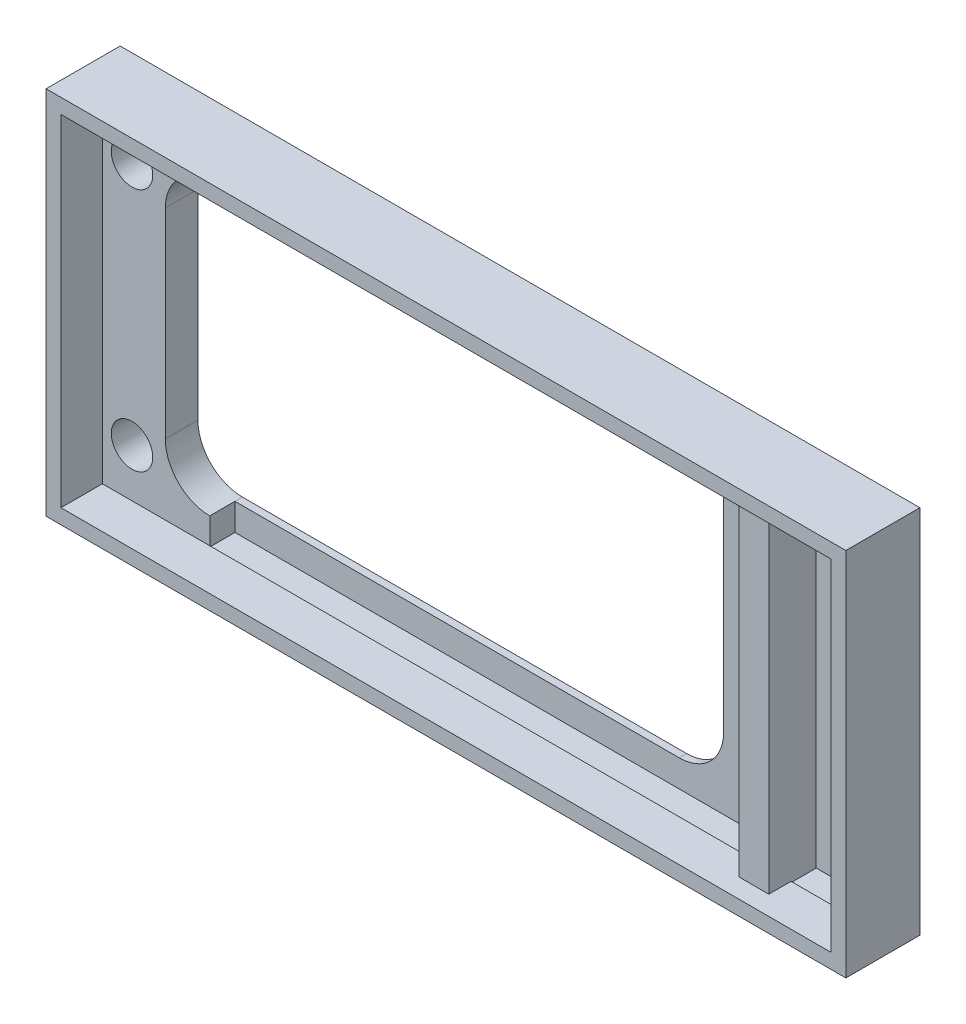
SolidWorks part; units mm, degrees
ref_plane "Front Plane" through (0, 0, 0) normal (0, 0, 1) x (1, 0, 0)
ref_plane "Top Plane" through (0, 0, 0) normal (0, 1, 0) x (1, 0, 0)
ref_plane "Right Plane" through (0, 0, 0) normal (1, 0, 0) x (0, 0, -1)
sketch "Sketch1" plane through (0, 0, 0) normal (0, 0, 1) x (1, 0, 0)
  line L1 (-26, -11.5) -> (26, -11.5)
  line L2 (-26, -11.5) -> (-26, 11.5)
  line L3 (-26, 11.5) -> (26, 11.5)
  line L4 (26, -11.5) -> (26, 11.5)
  line L5 (-26, -11.5) -> (26, 11.5) construction
  line L6 (-26, 11.5) -> (26, -11.5) construction
  line L7 (-27, -12.5) -> (27, -12.5)
  line L8 (-27, -12.5) -> (-27, 12.5)
  line L9 (-27, 12.5) -> (27, 12.5)
  line L10 (27, -12.5) -> (27, 12.5)
  line L11 (-27, -12.5) -> (27, 12.5) construction
  line L12 (-27, 12.5) -> (27, -12.5) construction
  point P0 (0, 0)
  point P6 (0, 0)
  dimension "D1" = 23
  dimension "D2" = 52
  dimension "D3" = 1
  dimension "D4" = 1
extrude "Boss-Extrude1" add sketch "Sketch1" along normal blind 5
sketch "Sketch2" plane through (0, 0, 0) normal (0, 0, -1) x (-1, 0, 0)
  line L0 (-23, 8.25) -> (-23, -8.25) construction
  line L1 (-11.25, -9.75) -> (18.75, -9.75)
  line L2 (-14.25, -6.75) -> (-14.25, 6.75)
  line L3 (-11.25, 9.75) -> (18.75, 9.75)
  line L4 (21.75, -6.75) -> (21.75, 6.75)
  line L5 (-14.25, -9.75) -> (21.75, 9.75) construction
  line L6 (-14.25, 9.75) -> (21.75, -9.75) construction
  line L7 (-27, 12.5) -> (27, 12.5) construction
  line L8 (27, -12.5) -> (-27, -12.5)
  line L9 (27, -12.5) -> (27, 12.5)
  line L10 (27, 12.5) -> (-27, 12.5)
  line L11 (-27, -12.5) -> (-27, 12.5)
  line L12 (27, -12.5) -> (-27, 12.5) construction
  line L13 (27, 12.5) -> (-27, -12.5) construction
  line L14 (-27, -12.5) -> (-27, 12.5) construction
  line L15 (26, 11.5) -> (26, -11.5) construction
  line L19 (27, 12.5) -> (27, -12.5) construction
  line L28 (27, -12.5) -> (-27, -12.5) construction
  line L29 (24, 8.25) -> (24, -8.25) construction
  arc A0 (18.75, 9.75) -> (21.75, 6.75) centre (18.75, 6.75) cw
  arc A1 (18.75, -9.75) -> (21.75, -6.75) centre (18.75, -6.75) ccw
  arc A2 (-11.25, -9.75) -> (-14.25, -6.75) centre (-11.25, -6.75) cw
  arc A3 (-14.25, 6.75) -> (-11.25, 9.75) centre (-11.25, 6.75) cw
  circle A4 centre (24, 8.25) radius 1.4
  circle A5 centre (24, -8.25) radius 1.4
  circle A6 centre (-23, 8.25) radius 1.4
  circle A7 centre (-23, -8.25) radius 1.4
  point P0 (0, 0)
  point P6 (0, 0)
  point P35 (24, 0)
  point P39 (-14.25, 0)
  point P40 (3.75, 0)
  point P44 (-23, 0)
  dimension "D3" = 3
  dimension "D4" = 2.8
  dimension "D5" = 2.8
  dimension "D6" = 2
  dimension "D7" = 2
  dimension "D8" = 36
  dimension "D9" = 16.5
  dimension "D10" = 4.25
  dimension "D11" = 4
  dimension "D12" = 16.5
  dimension "D14" = 4
  dimension "D2" = 19.5
extrude "Boss-Extrude2" add sketch "Sketch2" against normal blind 2.2
sketch "Sketch3" plane through (0, 0, 2.2) normal (0, 0, 1) x (1, 0, 0)
  line L1 (26, 11.5) -> (-18.75, 11.5)
  line L2 (26, 11.5) -> (26, -11.5719)
  line L3 (26, -11.5719) -> (-18.75, -11.5719)
  line L4 (-18.75, 11.5) -> (-18.75, -11.5719)
extrude "Cut-Extrude1" cut sketch "Sketch3" against normal blind 1.7
sketch "Sketch4" plane through (0, 0, 0.5) normal (0, 0, 1) x (1, 0, 0)
fillet "Fillet1" radius 1 1 edges at (-18.75, 10.625, 2.2)
sketch "Sketch5" plane through (0, 0, 0.5) normal (0, 0, 1) x (1, 0, 0)
  line L0 (26, 11.5) -> (-18.75, 11.5) construction
  line L1 (18.5, 11.5) -> (20.5, 11.5)
  line L2 (18.5, 11.5) -> (18.5, -11.5719)
  line L3 (18.5, -11.5719) -> (20.5, -11.5719)
  line L4 (20.5, 11.5) -> (20.5, -11.5719)
  line L5 (-18.75, -11.5719) -> (26, -11.5719) construction
  line L6 (-26, 11.5) -> (-26, -11.5) construction
  dimension "D1" = 44.5
  dimension "D2" = 2
extrude "Boss-Extrude3" add sketch "Sketch5" along normal blind 3.2
